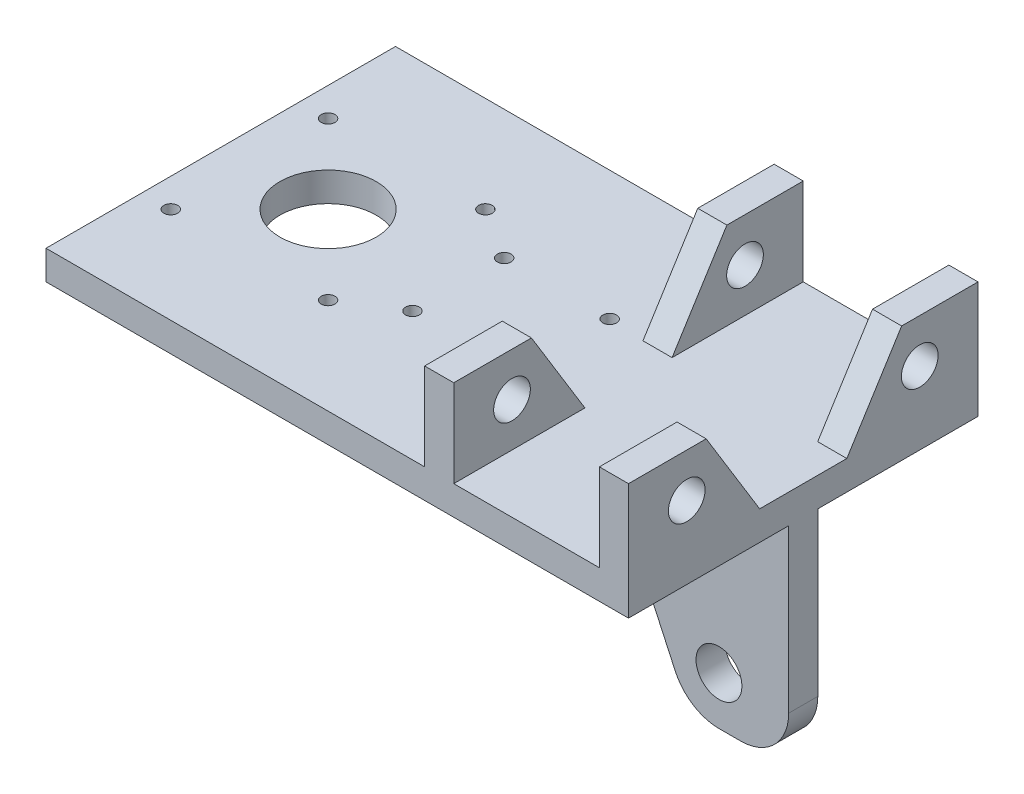
SolidWorks part; units mm, degrees
ref_plane "Front Plane" through (0, 0, 0) normal (0, 0, 1) x (1, 0, 0)
ref_plane "Top Plane" through (0, 0, 0) normal (0, 1, 0) x (1, 0, 0)
ref_plane "Right Plane" through (0, 0, 0) normal (1, 0, 0) x (0, 0, -1)
sketch "Sketch2" plane through (0, 0, 0) normal (0, 1, 0) x (1, 0, 0)
  line L0 (-40.1, 0) -> (-85.4523, 0) construction
  line L1 (-63.5, 38.1) -> (63.5, 38.1)
  line L2 (-63.5, 38.1) -> (-63.5, -38.1)
  line L3 (-63.5, -38.1) -> (63.5, -38.1)
  line L4 (63.5, 38.1) -> (63.5, -38.1)
  line L5 (-63.5, 38.1) -> (63.5, -38.1) construction
  line L6 (-63.5, -38.1) -> (63.5, 38.1) construction
  line L7 (-40.1, 0) -> (-40.1, 66.6915) construction
  line L8 (-0.2, 61.9582) -> (-0.2, -58.7007) construction
  line L9 (-87.3066, 0) -> (90.7374, 0) construction
  circle A0 centre (-40.1, 0) radius 10.5
  circle A3 centre (11.3, 10) radius 1.5
  circle A5 centre (-57.25, 17.15) radius 1.5
  circle A6 centre (-57.25, -17.15) radius 1.5
  circle A11 centre (-11.7, 10) radius 1.5
  circle A12 centre (-22.95, -17.15) radius 1.5
  circle A13 centre (-22.95, 17.15) radius 1.5
  circle A14 centre (11.3, -10) radius 1.5
  circle A15 centre (-11.7, -10) radius 1.5
  point P0 (0, 0)
  dimension "D3" = 21
  dimension "D5" = 23
  dimension "D7" = 3
  dimension "D10" = 3
  dimension "D1" = 76.2
  dimension "D2" = 127
  dimension "D4" = 103.6
  dimension "D6" = 10
  dimension "D11" = 17.15
  dimension "D12" = 17.15
  dimension "D14" = 52.2
extrude "Boss-Extrude1" add sketch "Sketch2" along normal blind 6.35
sketch "Sketch3" plane through (63.5, 0, 0) normal (1, 0, 0) x (0, 0, -1)
  line L0 (-38.1, 6.35) -> (38.1, 6.35) construction
  line L1 (-38.1, 0) -> (38.1, 0)
  line L2 (-38.1, 0) -> (-38.1, 25.4)
  line L3 (-38.1, 25.4) -> (-21.1655, 25.4)
  line L4 (38.1, 0) -> (38.1, 25.4)
  line L5 (21.4519, 25.4) -> (38.1, 25.4)
  line L8 (9.5, 6.35) -> (-9.5, 6.35)
  line L10 (0, 25.4) -> (-9.5, 6.35) construction
  line L11 (9.5, 6.35) -> (0, 25.4) construction
  line L12 (-21.1655, 25.4) -> (-9.5, 6.35)
  line L13 (21.4519, 25.4) -> (9.5, 6.35)
  circle A0 centre (-25.4, 15.875) radius 4
  circle A1 centre (25.4, 15.875) radius 4
  point P11 (0, 25.4)
  dimension "D2" = 8
  dimension "D3" = 8
  dimension "D1" = 19.05
  dimension "D4" = 25.4
  dimension "D5" = 25.4
  dimension "D6" = 9.525
  dimension "D7" = 9.525
  dimension "D9" = 19
extrude "Boss-Extrude2" add sketch "Sketch3" against normal blind 6.35
pattern_linear "LPattern1" count 2 spacing 38.1 along (-1, 0, 0) of "Boss-Extrude2"
sketch "Sketch4" plane through (0, 0, -38.1) normal (0, 0, -1) x (-1, 0, 0)
  line L1 (63.5, 0) -> (-63.5, 0) construction
  line L3 (-63.5, 0) -> (-20.4, 0)
  line L6 (-63.5, 25.4) -> (-63.5, 0) construction
  line L7 (-63.5, 0) -> (-63.5, -35.4)
  line L8 (-53, -45.9) -> (-48.3, -45.9)
  line L9 (-20.4, 0) -> (-38.7662, -39.7995)
  line L10 (0.2, 27.0446) -> (0.2, -69.0378) construction
  line L11 (66.5133, -16.5) -> (-94.0817, -16.5) construction
  line L12 (-63.5, 0) -> (63.5, 0) construction
  circle A0 centre (-48.3, -35.4) radius 5
  arc A1 (-48.3, -45.9) -> (-38.7662, -39.7995) centre (-48.3, -35.4) ccw
  arc A2 (-63.5, -35.4) -> (-53, -45.9) centre (-53, -35.4) ccw
  dimension "D2" = 10
  dimension "D5" = 21
  dimension "D7" = 10.5
  dimension "D1" = 48.5
  dimension "D3" = 18.9
  dimension "D4" = 63.7
  dimension "D6" = 16.5
extrude "Boss-Extrude3" add sketch "Sketch4" against normal mid plane 6.35 from offset 38.1
